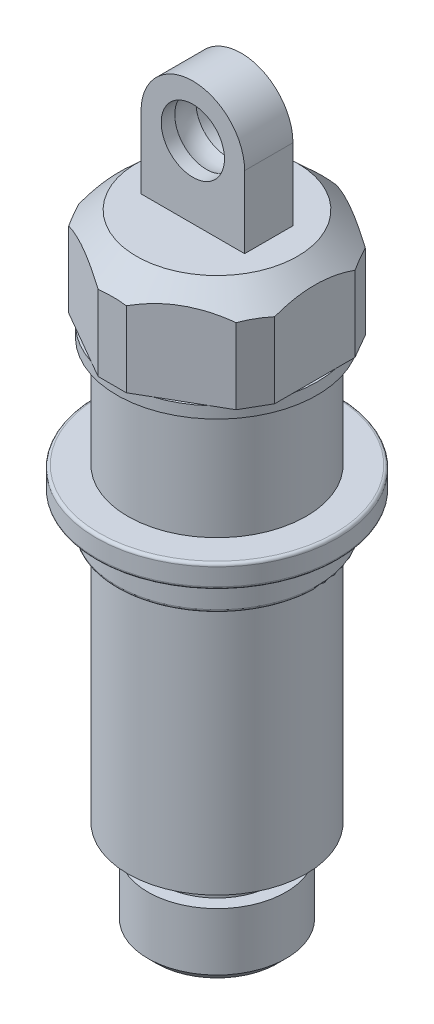
SolidWorks part; units mm, degrees
ref_plane "Front Plane" through (0, 0, 0) normal (0, 0, 1) x (1, 0, 0)
ref_plane "Top Plane" through (0, 0, 0) normal (0, 1, 0) x (1, 0, 0)
ref_plane "Right Plane" through (0, 0, 0) normal (1, 0, 0) x (0, 0, -1)
sketch "Sketch1" plane through (0, 0, 0) normal (0, 0, 1) x (1, 0, 0)
  line L0 (0, 45.5) -> (0, 0) construction
  line L1 (0, 0) -> (6, 0)
  line L2 (6, 0) -> (6, 5.75)
  line L3 (6, 5.75) -> (4.875, 5.75)
  line L4 (4.875, 5.75) -> (4.875, 6.5)
  line L5 (4.875, 6.5) -> (7.75, 8)
  line L6 (7.75, 8) -> (7.75, 44.5)
  line L7 (7.75, 44.5) -> (8.7, 44.5)
  line L8 (8.7, 44.5) -> (8.7, 45.5)
  line L10 (8.7, 45.5) -> (0, 45.5)
  line L12 (0, 45.5) -> (0, 0)
  dimension "D2" = 45.5
  dimension "D3" = 1
  dimension "D4" = 5.75
  dimension "D5" = 0.75
  dimension "D6" = 1.5
  dimension "D7" = 7.75
  dimension "D8" = 6
  dimension "D9" = 4.875
  dimension "D10" = 8.7
revolve "Revolve1" add sketch "Sketch1" angle 360 about L0
sketch "Sketch3" plane through (0, 45.5, 0) normal (0, 1, 0) x (1, 0, 0)
  line L1 (0, 9.815) -> (-8.5, 4.9075)
  line L2 (-8.5, 4.9075) -> (-8.5, -4.9075)
  line L3 (-8.5, -4.9075) -> (0, -9.815)
  line L4 (0, -9.815) -> (8.5, -4.9075)
  line L5 (8.5, -4.9075) -> (8.5, 4.9075)
  line L6 (8.5, 4.9075) -> (0, 9.815)
  circle A0 centre (0, 0) radius 8.5 construction
extrude "Boss-Extrude1" add sketch "Sketch3" along normal blind 8.6
chamfer "Chamfer1" distance 1.414 angle 30 6 edges at (-8.5, 49.8, 4.9075) (-8.5, 49.8, -4.9075) (0, 49.8, -9.815) (8.5, 49.8, -4.9075) (8.5, 49.8, 4.9075) (0, 49.8, 9.815)
sketch "Sketch5" plane through (0, 0, 0) normal (0, 0, 1) x (1, 0, 0)
  line L0 (7.75, 34.902) -> (10.5, 34.902)
  line L1 (7.75, 8) -> (7.75, 44.5) construction
  line L2 (10.5, 34.902) -> (10.5, 32.902)
  line L3 (10.5, 32.902) -> (8.7, 32.902)
  line L4 (8.7, 32.902) -> (8.7, 29.902)
  line L5 (8.7, 29.902) -> (7.75, 29.902)
  line L6 (7.75, 29.902) -> (7.75, 34.902)
  line L7 (-8.7, 44.5) -> (8.7, 44.5) construction
  line L8 (0, 0) -> (0, 33.2479) construction
  dimension "D1" = 9.598
  dimension "D2" = 8.7
  dimension "D3" = 10.5
  dimension "D4" = 5
  dimension "D5" = 3
revolve "Revolve2" add sketch "Sketch5" angle 360 about L8
fillet "Fillet1" radius 0.25 3 edges at (0, 29.902, -8.7) (0, 32.902, -10.5) (0, 34.902, -10.5)
sketch "Sketch6" plane through (0, 0, 0) normal (0, -1, 0) x (1, 0, 0)
  circle A0 centre (0, 0) radius 1.5
  dimension "D1" = 3
extrude "Cut-Extrude1" cut sketch "Sketch6" against normal blind 28
sketch "Sketch7" plane through (0, 0, 0) normal (0, 0, 1) x (1, 0, 0)
  line L0 (0, 54.1) -> (0, 60.35) construction
  line L1 (-1.2246, 54.1) -> (1.2246, 54.1) construction
  line L2 (4.5, 60.35) -> (4.5, 54.1)
  line L3 (1.2246, 54.1) -> (7.2754, 54.1) construction
  line L4 (-4.5, 60.35) -> (-4.5, 54.1)
  line L5 (-7.2754, 54.1) -> (-1.2246, 54.1) construction
  line L6 (-4.5, 54.1) -> (4.5, 54.1)
  arc A0 (4.5, 60.35) -> (-4.5, 60.35) centre (0, 60.35) ccw
  dimension "D2" = 9
  dimension "D1" = 6.25
extrude "Boss-Extrude2" add sketch "Sketch7" along normal mid plane 4.2
sketch "Sketch8" plane through (0, 0, 0) normal (0, 0, 1) x (1, 0, 0)
  line L0 (0, 54.1) -> (0, 63.25) construction
  line L1 (-4.5, 54.1) -> (4.5, 54.1) construction
  line L2 (0, 63.25) -> (0, 57.45)
  arc A0 (0, 57.45) -> (0, 63.25) centre (0, 60.35) ccw
  dimension "D1" = 5.8
revolve "Cut-Revolve1" cut sketch "Sketch8" angle 360 about L0
sketch "Sketch9" plane through (0, 0, 2.1) normal (0, 0, 1) x (1, 0, 0)
  circle A0 centre (0, 60.35) radius 2.75
  dimension "D1" = 5.5
extrude "Cut-Extrude2" cut sketch "Sketch9" against normal blind 4.2
sketch "Sketch10" plane through (0, 0, 0) normal (0, 0, 1) x (1, 0, 0)
  line L0 (7, 54.1) -> (8.5, 52.7)
  line L1 (1.2246, 54.1) -> (7.2754, 54.1) construction
  line L2 (8.5, 54.1) -> (8.5, 45.5) construction
  line L3 (8.5, 52.7) -> (10.1247, 51.1836)
  line L4 (10.1247, 53.9194) -> (7, 56.8358)
  line L5 (7, 56.8358) -> (7, 54.1)
  line L6 (-4.5, 54.1) -> (4.5, 54.1) construction
  line L7 (0, 0) -> (0, 63.5668) construction
  line L8 (10.1247, 51.1836) -> (10.1247, 53.9194)
  point P6 (0, 54.1)
  dimension "D1" = 7.2
  dimension "D2" = 7
  dimension "D3" = 2
  dimension "D4" = 2.2224
revolve "Cut-Revolve2" cut sketch "Sketch10" angle 360 about L7
chamfer "Chamfer3" distance 0.75 angle 45 1 edges at (-6, 0, 0)
